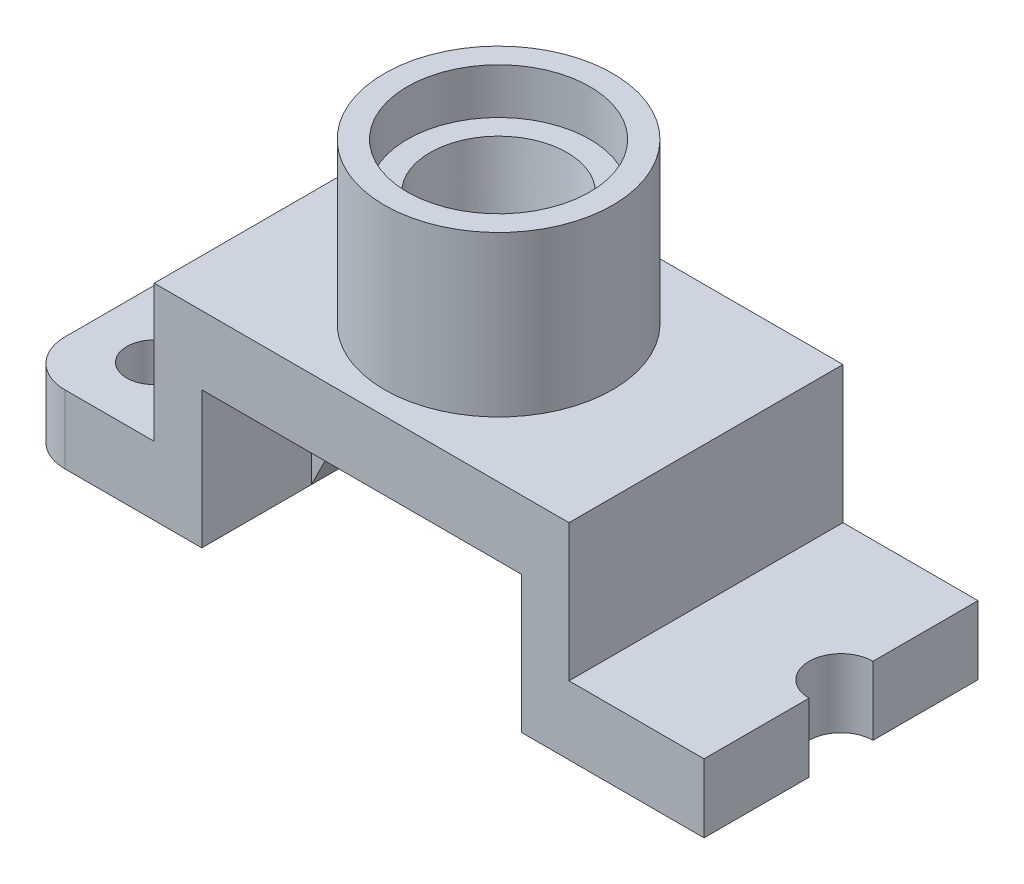
SolidWorks part; units mm, degrees
ref_plane "Front Plane" through (0, 0, 0) normal (0, 0, 1) x (1, 0, 0)
ref_plane "Top Plane" through (0, 0, 0) normal (0, 1, 0) x (1, 0, 0)
ref_plane "Right Plane" through (0, 0, 0) normal (1, 0, 0) x (0, 0, -1)
sketch "Sketch1" plane through (0, 0, 0) normal (0, 0, 1) x (1, 0, 0)
  line L0 (-75, 0) -> (-35, 0)
  line L1 (-35, 0) -> (-35, 30)
  line L2 (-35, 30) -> (35, 30)
  line L3 (35, 30) -> (35, 0)
  line L4 (35, 0) -> (75, 0)
  line L5 (75, 0) -> (75, 15)
  line L6 (75, 15) -> (45.4225, 15)
  line L7 (45.4225, 15) -> (45.4225, 45)
  line L8 (45.4225, 45) -> (-45.4225, 45)
  line L9 (-45.4225, 45) -> (-45.4225, 15)
  line L10 (-45.4225, 15) -> (-75, 15)
  line L11 (-75, 15) -> (-75, 0)
  point P11 (0, 30)
  point P14 (0, 45)
  dimension "D1" = 70
  dimension "D2" = 40
  dimension "D3" = 15
  dimension "D4" = 15
  dimension "D5" = 45
extrude "Boss-Extrude1" add sketch "Sketch1" along normal mid plane 60
sketch "Sketch2" plane through (0, 0, 0) normal (0, 0, 1) x (1, 0, 0)
  line L0 (35, 30) -> (35, 0) construction
  line L1 (-35, 30) -> (35, 30) construction
  line L2 (-35, 0) -> (-35, 30) construction
  line L3 (35, 30) -> (35, 0)
  line L4 (-35, 30) -> (-20, 30)
  line L5 (-35, 0) -> (-35, 30)
  line L6 (-35, 0) -> (-20, 30)
  line L7 (35, 0) -> (20, 30)
  line L8 (20, 30) -> (35, 30)
  dimension "D1" = 15
  dimension "D2" = 15
extrude "Boss-Extrude2" add sketch "Sketch2" along normal mid plane 12 contours L5 L6 L4 | L8 L7 L3
sketch "Sketch3" plane through (0, 15, 0) normal (0, 1, 0) x (1, 0, 0)
  line L0 (-45.4225, 30) -> (-75, 30) construction
  line L1 (-45.4225, -30) -> (-75, -30) construction
  circle A0 centre (-60.4225, -15) radius 6
  circle A1 centre (-60.4225, 15) radius 6
  point P8 (-61.0111, -16.1339)
  point P10 (-60.547, -15.8757)
  dimension "D1" = 12
  dimension "D2" = 15
  dimension "D3" = 15
  dimension "D4" = 15
  dimension "D5" = 15
extrude "Cut-Extrude1" cut sketch "Sketch3" against normal through all
fillet "Fillet1" radius 10 2 edges at (-75, 7.5, -30) (-75, 7.5, 30)
sketch "Sketch4" plane through (0, 15, 0) normal (0, 1, 0) x (1, 0, 0)
  line L0 (75, -30) -> (75, 30) construction
  circle A0 centre (75, 0) radius 7
  dimension "D1" = 14
extrude "Cut-Extrude2" cut sketch "Sketch4" against normal blind 22
sketch "Sketch5" plane through (0, 45, 0) normal (0, 1, 0) x (1, 0, 0)
  circle A0 centre (0, 0) radius 25
  dimension "D1" = 50
extrude "Boss-Extrude3" add sketch "Sketch5" along normal blind 35
sketch "Sketch6" plane through (0, 80, 0) normal (0, 1, 0) x (1, 0, 0)
  circle A0 centre (0, 0) radius 20
  dimension "D1" = 40
extrude "Cut-Extrude3" cut sketch "Sketch6" against normal blind 10
sketch "Sketch7" plane through (0, 70, 0) normal (0, 1, 0) x (1, 0, 0)
  circle A0 centre (0, 0) radius 15
  dimension "D1" = 30
sketch "Sketch8" plane through (0, 30, 0) normal (0, -1, 0) x (1, 0, 0)
  circle A0 centre (0, 0) radius 10
  circle A1 centre (0, 0) radius 15 construction
  dimension "D1" = 20
loft "Cut-Loft1" cut profiles "Sketch7", "Sketch8"
